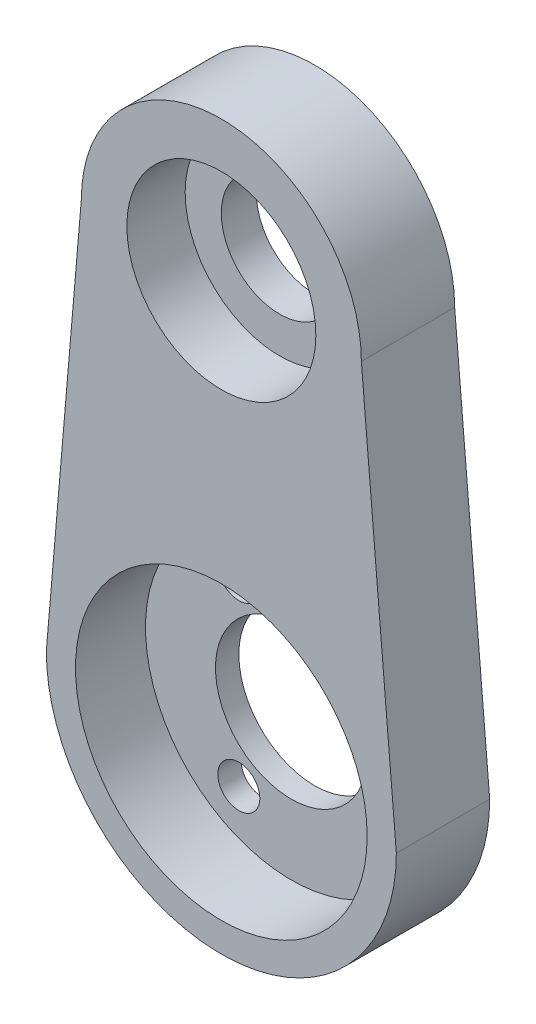
SolidWorks part; units mm, degrees
ref_plane "Plan de face" through (0, 0, 0) normal (0, 0, 1) x (1, 0, 0)
ref_plane "Plan de dessus" through (0, 0, 0) normal (0, 1, 0) x (1, 0, 0)
ref_plane "Plan de droite" through (0, 0, 0) normal (1, 0, 0) x (0, 0, -1)
sketch "Esquisse1" plane through (0, 0, 0) normal (0, 0, 1) x (1, 0, 0)
  line L0 (-16.3093, 0) -> (24.5372, 0) construction
  line L1 (12, 0) -> (15, -35)
  line L2 (-12, 0) -> (-15, -35)
  line L3 (-15, -35) -> (15, -35) construction
  line L4 (0, 0) -> (0, -35) construction
  arc A0 (-12, 0) -> (12, 0) centre (0, 0) cw
  arc A1 (-15, -35) -> (15, -35) centre (0, -35) ccw
  dimension "D1" = 12
  dimension "D2" = 15
  dimension "D3" = 35
extrude "Boss.-Extru.1" add sketch "Esquisse1" along normal blind 8
sketch "Esquisse2" plane through (0, 0, 8) normal (0, 0, 1) x (1, 0, 0)
  line L0 (0, 0) -> (0, -50) construction
  line L1 (15, -35) -> (-15, -35) construction
  circle A0 centre (0, -35) radius 6.5
  arc A1 (-15, -35) -> (15, -35) centre (0, -35) ccw construction
extrude "Enlèv. mat.-Extru.1" cut sketch "Esquisse2" against normal blind 10
sketch "Esquisse3" plane through (0, 0, 8) normal (0, 0, 1) x (1, 0, 0)
  line L0 (0, -35) -> (0, 0) construction
  line L1 (0, -35) -> (-4.5, -27.2058) construction
  line L2 (0, -35) -> (9, -35) construction
  line L3 (0, -35) -> (-4.5, -42.7942) construction
  circle A0 centre (9, -35) radius 1.8
  circle A1 centre (-4.5, -27.2058) radius 1.8
  circle A2 centre (-4.5, -42.7942) radius 1.8
  dimension "D1" = 120
  dimension "D2" = 120
  dimension "D3" = 120
extrude "Enlèv. mat.-Extru.2" cut sketch "Esquisse3" against normal blind 10
ref_plane "Plan1" through (0, 10, 0) normal (0, 1, 0) x (1, 0, 0)
sketch "Esquisse5" plane through (0, 0, 8) normal (0, 0, 1) x (1, 0, 0)
  circle A0 centre (0, -35) radius 12.5
  dimension "D1" = 25
extrude "Enlèv. mat.-Extru.5" cut sketch "Esquisse5" against normal blind 6
sketch "Esquisse19" plane through (0, 0, 8) normal (0, 0, 1) x (1, 0, 0)
  circle A0 centre (0, 0) radius 8.1
extrude "Enlèv. mat.-Extru.6" cut sketch "Esquisse19" against normal blind 10 contours A0
sketch "Esquisse21" plane through (0, 0, 0) normal (0, 0, -1) x (-1, 0, 0)
  line L0 (-12, 0) -> (-15, -35)
  line L1 (12, 0) -> (15, -35)
  circle A0 centre (0, 0) radius 12
  circle A1 centre (0, -35) radius 15
sketch "Esquisse22" plane through (0, 0, 0) normal (0, 0, -1) x (-1, 0, 0)
  circle A0 centre (0, 0) radius 8.1
  circle A1 centre (0, 0) radius 5
extrude "Boss.-Extru.2" add sketch "Esquisse22" against normal blind 3
